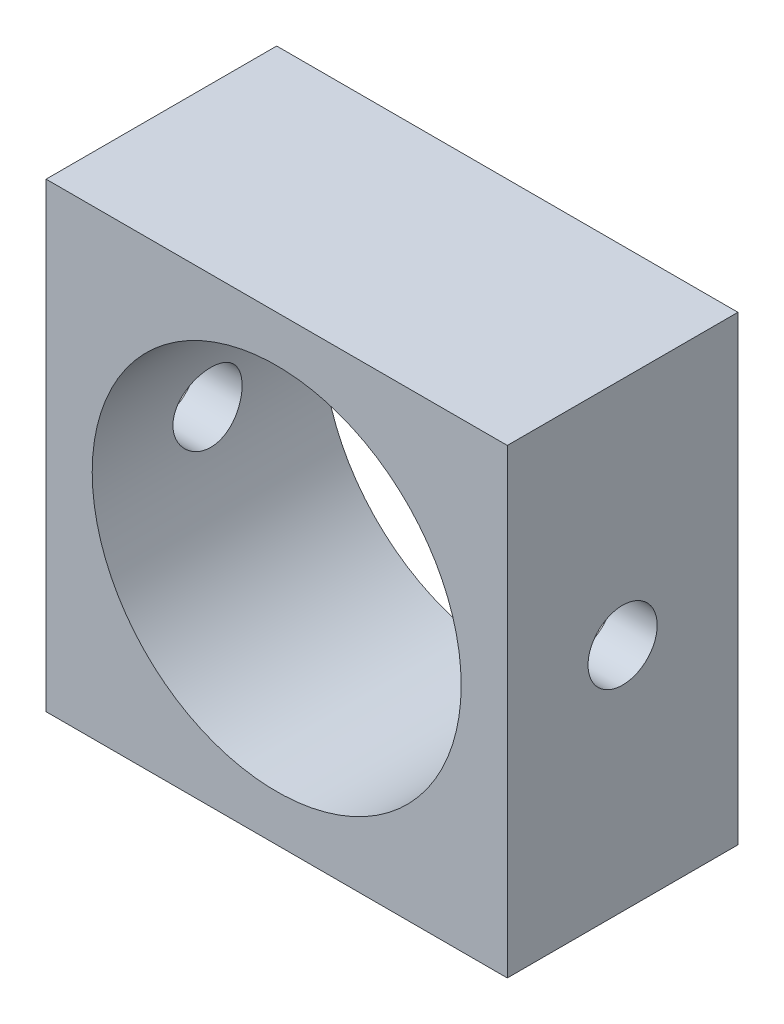
SolidWorks part; units mm, degrees
material "5454-H32"
ref_plane "Front Plane" through (0, 0, 0) normal (0, 0, 1) x (1, 0, 0)
ref_plane "Top Plane" through (0, 0, 0) normal (0, 1, 0) x (1, 0, 0)
ref_plane "Right Plane" through (0, 0, 0) normal (1, 0, 0) x (0, 0, -1)
sketch "Sketch1" plane through (0, 0, 0) normal (0, 0, 1) x (1, 0, 0)
  line L1 (-10, -10) -> (10, -10)
  line L2 (-10, -10) -> (-10, 10)
  line L3 (-10, 10) -> (10, 10)
  line L4 (10, -10) -> (10, 10)
  line L5 (-10, -10) -> (10, 10) construction
  line L6 (-10, 10) -> (10, -10) construction
  circle A0 centre (0, 0) radius 8
extrude "Boss-Extrude1" add sketch "Sketch1" along normal blind 10
sketch "Sketch4" plane through (10, 0, 0) normal (1, 0, 0) x (0, 0, -1)
  circle A0 centre (-5, 0) radius 1.5
extrude "Cut-Extrude1" cut sketch "Sketch4" against normal blind 20
